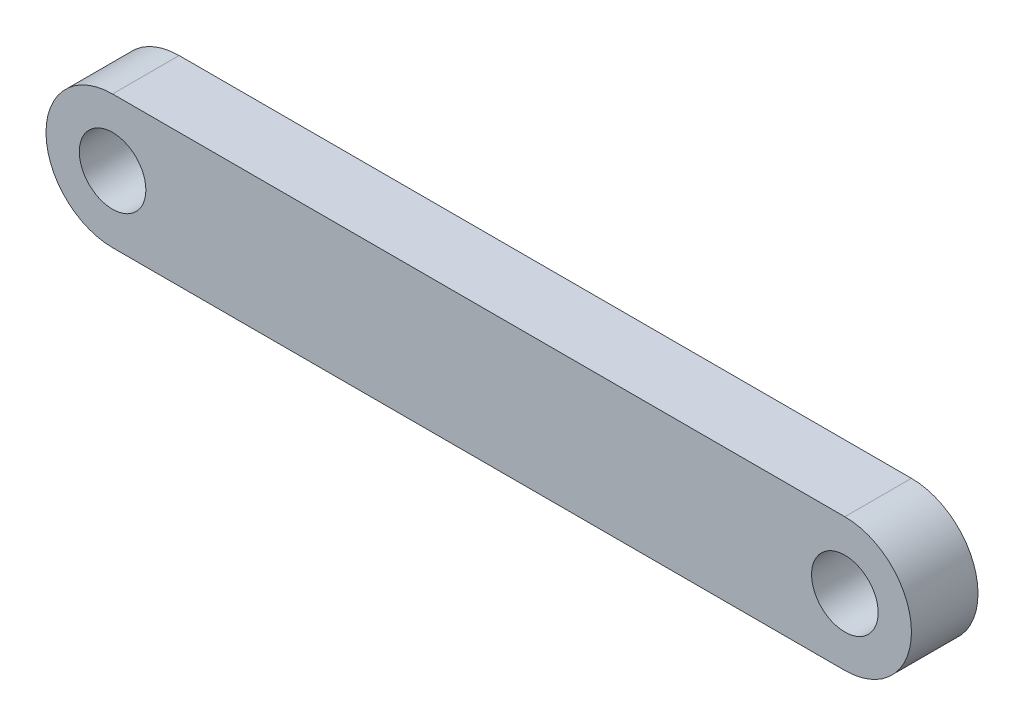
SolidWorks part; units mm, degrees
material "普通碳钢"
ref_plane "前视基准面" through (0, 0, 0) normal (0, 0, 1) x (1, 0, 0)
ref_plane "上视基准面" through (0, 0, 0) normal (0, 1, 0) x (1, 0, 0)
ref_plane "右视基准面" through (0, 0, 0) normal (1, 0, 0) x (0, 0, -1)
sketch "草图1" plane through (0, 0, 0) normal (0, 0, 1) x (1, 0, 0)
  line L0 (0, 0) -> (110, 0) construction
  line L1 (0, -10) -> (110, -10)
  line L2 (0, 10) -> (110, 10)
  arc A0 (0, 10) -> (0, -10) centre (0, 0) ccw
  arc A1 (110, 10) -> (110, -10) centre (110, 0) cw
  dimension "D3" = 110
  dimension "D1" = 10
  dimension "D2" = 10
extrude "凸台-拉伸1" add sketch "草图1" along normal blind 10
sketch "草图2" plane through (0, 0, 10) normal (0, 0, 1) x (1, 0, 0)
  circle A0 centre (0, 0) radius 5
  dimension "D1" = 10
extrude "切除-拉伸1" cut sketch "草图2" against normal blind 10
sketch "草图3" plane through (0, 0, 10) normal (0, 0, 1) x (1, 0, 0)
  circle A0 centre (110, 0) radius 5
  dimension "D1" = 10
extrude "切除-拉伸2" cut sketch "草图3" against normal blind 10
